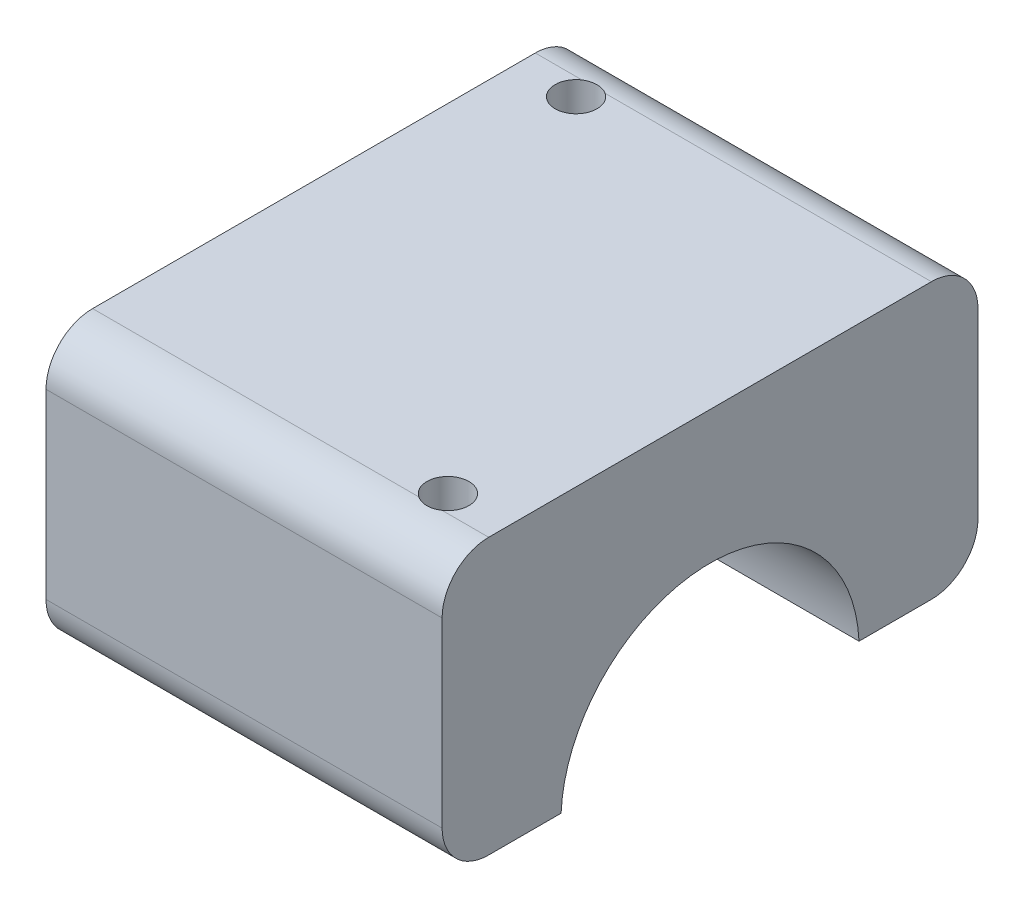
SolidWorks part; units mm, degrees
ref_plane "Front Plane" through (0, 0, 0) normal (0, 0, 1) x (1, 0, 0)
ref_plane "Top Plane" through (0, 0, 0) normal (0, 1, 0) x (1, 0, 0)
ref_plane "Right Plane" through (0, 0, 0) normal (1, 0, 0) x (0, 0, -1)
sketch "Sketch1" plane through (0, 0, 0) normal (1, 0, 0) x (0, 0, -1)
  line L0 (-19, 0.6) -> (19, 0.6)
  line L1 (23, 4.6) -> (23, 20.221)
  line L2 (19, 24.221) -> (-19, 24.221)
  line L3 (-23, 20.221) -> (-23, 4.6)
  arc A0 (19, 0.6) -> (23, 4.6) centre (19, 4.6) ccw
  arc A1 (23, 20.221) -> (19, 24.221) centre (19, 20.221) ccw
  arc A2 (-19, 24.221) -> (-23, 20.221) centre (-19, 20.221) ccw
  arc A3 (-23, 4.6) -> (-19, 0.6) centre (-19, 4.6) ccw
extrude "Boss-Extrude1" add sketch "Sketch1" along normal mid plane 34
sketch "Sketch2" plane through (0, 0, 0) normal (1, 0, 0) x (0, 0, -1)
  circle A0 centre (0, 0) radius 12.8
extrude "Cut-Extrude1" cut sketch "Sketch2" against normal through all and the other way through all
ref_plane "Plane1" through (0, 0.6, 0) normal (0, 1, 0) x (1, 0, 0)
sketch "Sketch3" plane through (0, 0.6, 0) normal (0, 1, 0) x (1, 0, 0)
  circle A0 centre (12, -17.5) radius 1.8
  circle A1 centre (-12, 17.5) radius 1.8
extrude "Cut-Extrude2" cut sketch "Sketch3" along normal blind 24.221
